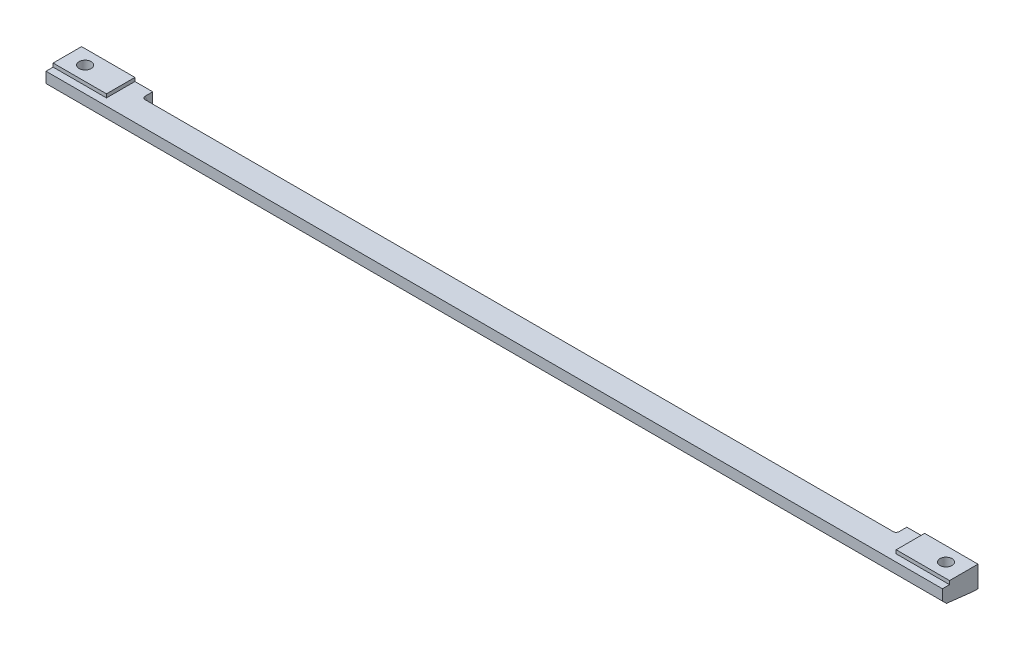
SolidWorks part; units mm, degrees
material "Д16Т ГОСТ 4784-74"
ref_plane "Спереди" through (0, 0, 0) normal (0, 0, 1) x (1, 0, 0)
ref_plane "Сверху" through (0, 0, 0) normal (0, 1, 0) x (1, 0, 0)
ref_plane "Справа" through (0, 0, 0) normal (1, 0, 0) x (0, 0, -1)
sketch "Эскиз1" plane through (0, 0, 0) normal (0, 0, 1) x (1, 0, 0)
  line L0 (0, 0) -> (0, 31.2218) construction
  line L1 (-126, 0) -> (126, 0)
  line L2 (126, 0) -> (126, 6)
  line L3 (126, 6) -> (111, 6)
  line L4 (111, 6) -> (111, 5)
  line L5 (111, 5) -> (-111, 5)
  line L6 (-111, 6) -> (-111, 5)
  line L7 (-126, 6) -> (-111, 6)
  line L8 (-126, 0) -> (-126, 6)
  point P9 (0, 5)
  dimension "D1" = 6
  dimension "D2" = 15
  dimension "D3" = 222
  dimension "D4" = 5
extrude "Бобышка-Вытянуть1" add sketch "Эскиз1" along normal blind 10
sketch "Эскиз5" plane through (0, 0, 0) normal (1, 0, 0) x (0, 0, -1)
  line L0 (0, 0) -> (-0.8, 0)
  line L1 (-10, 0) -> (0, 0) construction
  line L2 (-0.8, 0) -> (-3, 5)
  line L3 (-10, 5) -> (0, 5) construction
  line L4 (-3, 5) -> (0, 5)
  line L5 (0, 5) -> (0, 0)
  dimension "D1" = 0.8
  dimension "D2" = 3
extrude "Вырез-Вытянуть1" cut sketch "Эскиз5" against normal mid plane 212
fillet "Скругление1" radius 0.8 2 edges at (-106, 2.5, 1.9) (106, 2.5, 1.9)
sketch "Эскиз6" plane through (-126, 0, 0) normal (-1, 0, 0) x (0, 0, 1)
  line L0 (1.3, 0) -> (10, 1)
  line L1 (10, 0) -> (0, 0) construction
  line L2 (10, 6) -> (10, 0) construction
  line L3 (10, 1) -> (10, 0)
  line L4 (10, 0) -> (1.3, 0)
  dimension "D1" = 1.3
  dimension "D2" = 1
extrude "Вырез-Вытянуть2" cut sketch "Эскиз6" against normal through all
chamfer "Фаска1" distance 1 angle 45 1 edges at (0, 1, 10)
sketch "Эскиз7" plane through (0, 6, 0) normal (0, 1, 0) x (1, 0, 0)
  line L0 (-111, -10) -> (-111, 0) construction
  line L1 (-126, -10) -> (-111, -10)
  line L2 (-126, -10) -> (-126, -8)
  line L3 (-126, -8) -> (-111, -8)
  line L4 (-111, -10) -> (-111, -8)
  line L5 (126, -10) -> (126, 0) construction
  line L6 (111, -10) -> (126, -10)
  line L7 (111, -10) -> (111, -8)
  line L8 (111, -8) -> (126, -8)
  line L9 (126, -10) -> (126, -8)
  dimension "D1" = 2
  dimension "D2" = 2
extrude "Вырез-Вытянуть3" cut sketch "Эскиз7" against normal blind 1
hole_wizard "Отверстие обработанное метчиком M21" positions "Эскиз9" profile "Эскиз8" tap size "M2" standard "DIN"
sketch "Эскиз9" plane through (0, 0, 0) normal (0, 0, -1) x (-1, 0, 0)
  line L0 (111, 6) -> (126, 6) construction
  line L1 (126, 6) -> (126, 0) construction
  line L2 (-126, 0) -> (-126, 6) construction
  line L3 (-126, 6) -> (-111, 6) construction
  point P0 (-116, 3.5)
  point P1 (116, 3.5)
  dimension "D1" = 2.5
  dimension "D2" = 10
  dimension "D3" = 10
  dimension "D4" = 2.5
sketch "Эскиз8" plane through (116, 3.5, 0) normal (1, 0, 0) x (0, 1, 0)
  line L0 (0, 0) -> (0, 6.4807)
  line L1 (0, 6.4807) -> (0.8, 6)
  line L2 (0.8, 6) -> (0.8, 0.1299)
  line L3 (0.8, 0.1299) -> (1.025, 0)
  line L5 (1.025, 0) -> (0, 0)
  line L6 (-0.8, 0.1299) -> (-1.025, 0) construction
  line L10 (0, 6.4807) -> (-0.8, 6) construction
  line L11 (0, -6.35) -> (0, 107.95) construction
  dimension "Диаметр сверла" = 1.6
  dimension "Глубина сверла" = 6
  dimension "Диаметр передней зенковки" = 2.05
  dimension "Угол передней зенковки" = 120
  dimension "Угол заточки сверла" = 118
cosmetic thread "Отверстие резьбы1" parameters "D1"=4, "D2"=2
cosmetic thread "Отверстие резьбы2" parameters "D1"=4, "D2"=2
hole_wizard "Цековка для  винта с внутренним шестигранником M31" positions "Эскиз12" profile "Эскиз11" counterbore size "M3" standard "DIN" end condition through all
sketch "Эскиз12" plane through (0, 0, 0) normal (0, -1, 0) x (1, 0, 0)
  line L0 (-126, 8.8701) -> (-126, 1.3) construction
  line L1 (-126, 0) -> (-105.9971, 0) construction
  line L2 (126, 8.8701) -> (126, 1.3) construction
  point P0 (121, 4)
  point P1 (-121, 4)
  dimension "D1" = 5
  dimension "D2" = 4
  dimension "D3" = 5
sketch "Эскиз11" plane through (121, 0, 4) normal (1, 0, 0) x (0, 0, -1)
  line L0 (0, 0) -> (0, 6)
  line L1 (0, 6) -> (1.7, 6)
  line L3 (1.7, 6) -> (1.7, 3.6)
  line L4 (1.7, 3.6) -> (3.25, 3.6)
  line L5 (3.25, 3.6) -> (3.25, 0)
  line L7 (3.25, 0) -> (0, 0)
  line L11 (0, -6.35) -> (0, 107.95) construction
  dimension "Диаметр сквозного отверстия" = 3.4
  dimension "Глубина сквозного отверстия" = 6
  dimension "Диаметр цековки" = 6.5
  dimension "Глубина цековки" = 3.6
